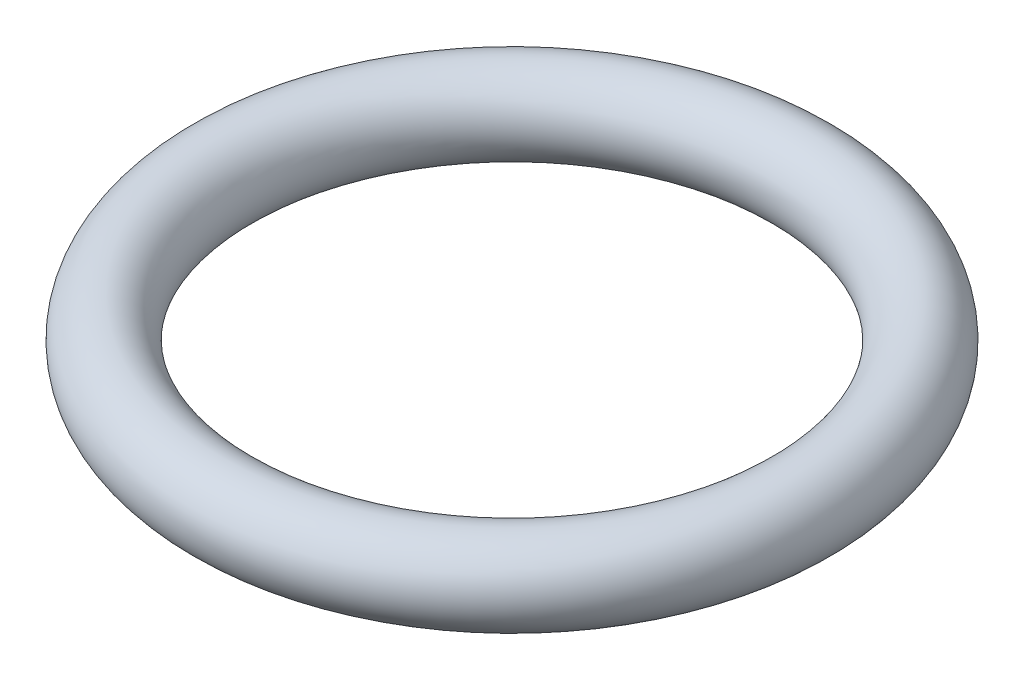
SolidWorks part; units mm, degrees
ref_plane "Front Plane" through (0, 0, 0) normal (0, 0, 1) x (1, 0, 0)
ref_plane "Top Plane" through (0, 0, 0) normal (0, 1, 0) x (1, 0, 0)
ref_plane "Right Plane" through (0, 0, 0) normal (1, 0, 0) x (0, 0, -1)
sketch "Sketch3" plane through (0, 0, 0) normal (0, 0, 1) x (1, 0, 0)
  line L0 (0, 21.25) -> (0, 19.472) construction
  circle A0 centre (6.2992, 20.361) radius 0.889
revolve "Revolve2" add sketch "Sketch3" angle 360 about L0
